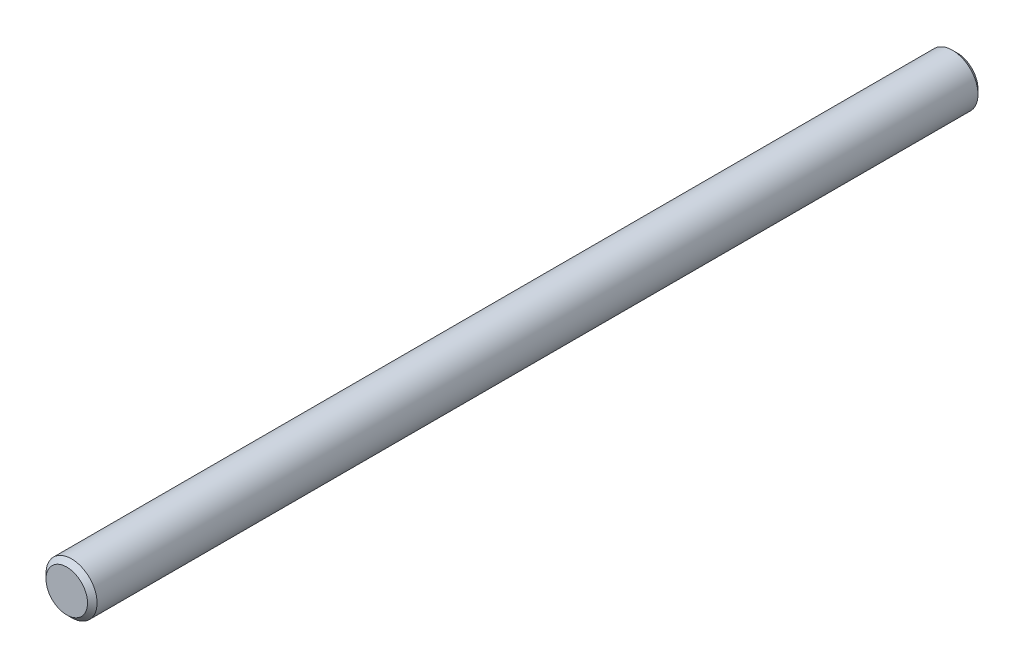
SolidWorks part; units mm, degrees
material "Alloy Steel"
ref_plane "Front Plane" through (0, 0, 0) normal (0, 0, 1) x (1, 0, 0)
ref_plane "Top Plane" through (0, 0, 0) normal (0, 1, 0) x (1, 0, 0)
ref_plane "Right Plane" through (0, 0, 0) normal (1, 0, 0) x (0, 0, -1)
sketch "Sketch1" plane through (0, 0, 0) normal (0, 0, 1) x (1, 0, 0)
  circle A0 centre (0, 0) radius 1.0922
  dimension "D1" = 2.1844
extrude "Extrude1" add sketch "Sketch1" against normal blind 38.1
cosmetic thread "Cosmetic Thread1" parameters "D2"=1.778
chamfer "Chamfer1" distance 0.2032 angle 45 2 edges at (1.0922, 0, -38.1) (1.0922, 0, 0)
